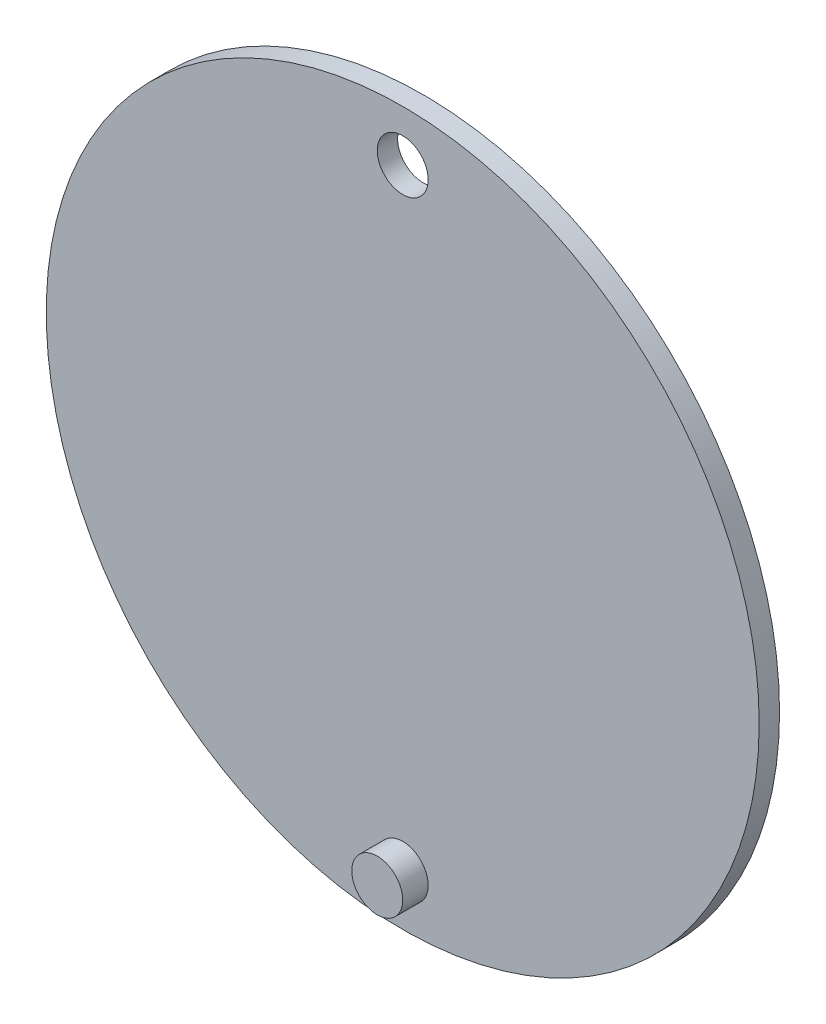
SolidWorks part; units mm, degrees
ref_plane "Front Plane" through (0, 0, 0) normal (0, 0, 1) x (1, 0, 0)
ref_plane "Top Plane" through (0, 0, 0) normal (0, 1, 0) x (1, 0, 0)
ref_plane "Right Plane" through (0, 0, 0) normal (1, 0, 0) x (0, 0, -1)
sketch "Sketch1" plane through (0, 0, 0) normal (0, 0, 1) x (1, 0, 0)
  line L0 (-169.7289, -88.9) -> (169.7289, -88.9) construction
  line L1 (-97.9706, 88.9) -> (97.9706, 88.9) construction
  circle A0 centre (0, 0) radius 88.9
  circle A1 centre (0, 0) radius 6.35
  circle A2 centre (0, -76.2) radius 6.35
  circle A3 centre (0, 76.2) radius 6.35
  point P7 (0, -88.9)
  point P14 (0, 88.9)
  dimension "D1" = 177.8
  dimension "D2" = 12.7
  dimension "D3" = 12.7
  dimension "D5" = 12.7
  dimension "D4" = 12.7
  dimension "D6" = 12.7
extrude "Boss-Extrude1" add sketch "Sketch1" along normal blind 5.08
sketch "Sketch2" plane through (0, 0, 0) normal (0, 0, 1) x (1, 0, 0)
  circle A0 centre (0, -76.2) radius 6.35
extrude "Boss-Extrude2" add sketch "Sketch2" along normal blind 11.43
ref_plane "Plane1" through (0, 0, 5.08) normal (0, 0, -1) x (-1, 0, 0)
sketch "Sketch3" plane through (0, 0, 5.08) normal (0, 0, 1) x (1, 0, 0)
  circle A0 centre (0, 0) radius 6.35
extrude "Boss-Extrude3" add sketch "Sketch3" against normal blind 50.8
